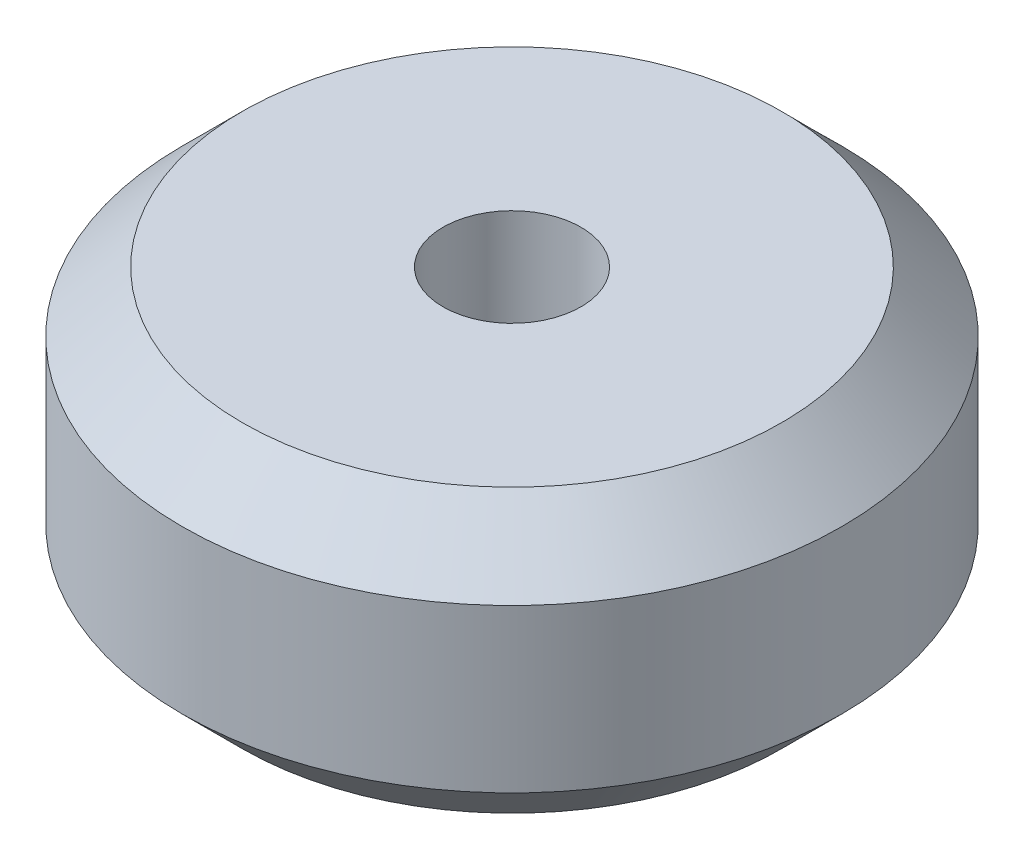
SolidWorks part; units mm, degrees
ref_plane "Front Plane" through (0, 0, 0) normal (0, 0, 1) x (1, 0, 0)
ref_plane "Top Plane" through (0, 0, 0) normal (0, 1, 0) x (1, 0, 0)
ref_plane "Right Plane" through (0, 0, 0) normal (1, 0, 0) x (0, 0, -1)
sketch "Sketch1" plane through (0, 0, 0) normal (0, 1, 0) x (1, 0, 0)
  circle A0 centre (0, 0) radius 11.945
  circle A1 centre (0, 0) radius 2.5
  dimension "D1" = 23.89
  dimension "D2" = 5
extrude "Boss-Extrude1" add sketch "Sketch1" along normal mid plane 10.23
chamfer "Chamfer1" distance 2.175 angle 45 2 edges at (0, -5.115, 11.945) (0, 5.115, 11.945)
